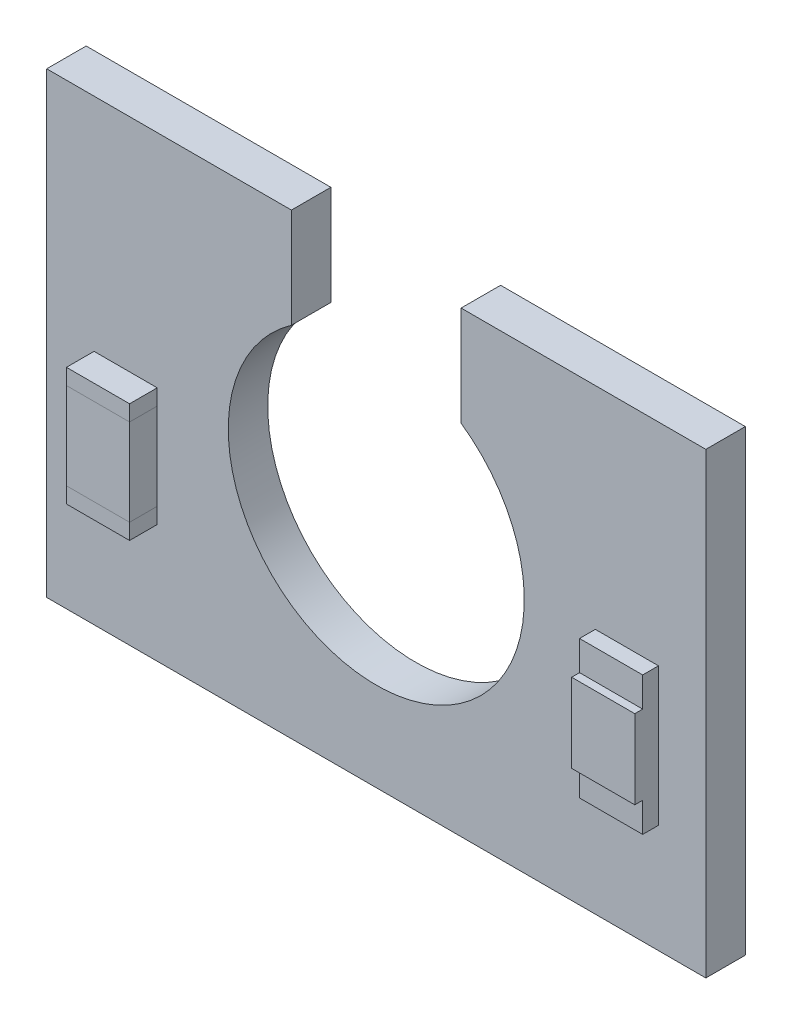
SolidWorks part; units mm, degrees
material "A-Glass Fiber"
ref_plane "Front Plane" through (0, 0, 0) normal (0, 0, 1) x (1, 0, 0)
ref_plane "Top Plane" through (0, 0, 0) normal (0, 1, 0) x (1, 0, 0)
ref_plane "Right Plane" through (0, 0, 0) normal (1, 0, 0) x (0, 0, -1)
sketch "BaseS" plane through (0, 0, 0) normal (0, 0, 1) x (1, 0, 0)
  line L1 (-8.35, 5.8) -> (8.35, 5.8)
  line L2 (-8.35, 5.8) -> (-8.35, -5.8)
  line L3 (-8.35, -5.8) -> (8.35, -5.8)
  line L4 (8.35, 5.8) -> (8.35, -5.8)
  line L5 (-8.35, 5.8) -> (8.35, -5.8) construction
  line L6 (-8.35, -5.8) -> (8.35, 5.8) construction
  point P0 (0, 0)
  dimension "D1" = 11.6
  dimension "D2" = 16.7
extrude "BASE" add sketch "BaseS" against normal blind 1
sketch "FastenerAccessS" plane through (0, 0, 0) normal (0, 0, 1) x (1, 0, 0)
  line L0 (0, -5.8) -> (0, 0.2) construction
  line L1 (-8.35, -5.8) -> (8.35, -5.8) construction
  line L2 (8.35, 5.8) -> (-8.35, 5.8) construction
  line L3 (-2.15, 5.8) -> (2.15, 5.8)
  line L4 (-2.15, 5.8) -> (-2.15, 3.2725)
  line L6 (2.15, 5.8) -> (2.15, 3.2725)
  arc A0 (-2.15, 3.2725) -> (2.15, 3.2725) centre (0, 0.2) ccw
  point P11 (0, 5.8)
  dimension "D1" = 7.5
  dimension "D2" = 6
  dimension "D3" = 4.3
extrude "FASTENER ACCESS" cut sketch "FastenerAccessS" against normal through all
sketch "SMDCapacitorBodyS" plane through (0, 0, 0) normal (0, 0, 1) x (1, 0, 0)
  line L0 (-8.35, -5.8) -> (8.35, -5.8) construction
  line L1 (-7.15, -0.2) -> (-5.55, -0.2)
  line L2 (-7.15, -0.2) -> (-7.15, -2.4)
  line L3 (-7.15, -2.4) -> (-5.55, -2.4)
  line L4 (-5.55, -0.2) -> (-5.55, -2.4)
  line L5 (-7.15, -0.2) -> (-5.55, -2.4) construction
  line L6 (-7.15, -2.4) -> (-5.55, -0.2) construction
  line L7 (-8.35, 5.8) -> (-8.35, -5.8) construction
  point P0 (-6.35, -1.3)
  dimension "D1" = 4.5
  dimension "D2" = 1.6
  dimension "D3" = 2.2
  dimension "D4" = 2
extrude "SMD CAPACITOR BODY" add sketch "SMDCapacitorBodyS" along normal blind 0.7 separate body
sketch "SMDCapacitorSolderBody1S" plane through (0, -2.4, 0) normal (0, -1, 0) x (1, 0, 0)
  line L4 (-7.15, 0) -> (-5.55, 0)
  line L5 (-5.55, 0) -> (-5.55, 0.7)
  line L6 (-5.55, 0.7) -> (-7.15, 0.7)
  line L7 (-7.15, 0.7) -> (-7.15, 0)
  line L8 (-7.15, 0) -> (-5.55, 0)
  line L9 (-5.55, 0) -> (-5.55, 0.7)
  line L10 (-5.55, 0.7) -> (-7.15, 0.7)
  line L11 (-7.15, 0.7) -> (-7.15, 0)
  dimension "D1" = 0
extrude "SMD CAPACITOR SOLDER BODY 1" add sketch "SMDCapacitorSolderBody1S" along normal blind 0.4 separate body
sketch "SMDCapacitorSolderBody2S" plane through (0, -0.2, 0) normal (0, 1, 0) x (1, 0, 0)
  line L4 (-5.55, 0) -> (-7.15, 0)
  line L5 (-7.15, 0) -> (-7.15, -0.7)
  line L6 (-7.15, -0.7) -> (-5.55, -0.7)
  line L7 (-5.55, -0.7) -> (-5.55, 0)
  line L8 (-5.55, 0) -> (-7.15, 0)
  line L9 (-7.15, 0) -> (-7.15, -0.7)
  line L10 (-7.15, -0.7) -> (-5.55, -0.7)
  line L11 (-5.55, -0.7) -> (-5.55, 0)
  dimension "D1" = 0
extrude "SMD CAPACITOR SOLDER BODY 2" add sketch "SMDCapacitorSolderBody2S" along normal blind 0.4 separate body
sketch "LEDS" plane through (0, 0, 0) normal (0, 0, 1) x (1, 0, 0)
  line L0 (-6.35, -1.3) -> (6.35, -1.3) construction
  line L1 (5.55, 0.45) -> (7.15, 0.45)
  line L2 (5.55, 0.45) -> (5.55, -3.05)
  line L3 (5.55, -3.05) -> (7.15, -3.05)
  line L4 (7.15, 0.45) -> (7.15, -3.05)
  line L5 (5.55, 0.45) -> (7.15, -3.05) construction
  line L6 (5.55, -3.05) -> (7.15, 0.45) construction
  line L7 (0, 0) -> (0, -1.3) construction
  point P0 (6.35, -1.3)
  dimension "D1" = 1.6
  dimension "D2" = 3.5
extrude "LED" add sketch "LEDS" along normal blind 0.4 separate body
sketch "LEDTS" plane through (0, 0, 0.4) normal (0, 0, 1) x (1, 0, 0)
  line L0 (7.15, -3.05) -> (7.15, 0.45) construction
  line L1 (5.55, -0.3) -> (7.15, -0.3)
  line L2 (5.55, -0.3) -> (5.55, -2.3)
  line L3 (5.55, -2.3) -> (7.15, -2.3)
  line L4 (7.15, -0.3) -> (7.15, -2.3)
  line L5 (5.55, -0.3) -> (7.15, -2.3) construction
  line L6 (5.55, -2.3) -> (7.15, -0.3) construction
  point P0 (6.35, -1.3)
  dimension "D1" = 2
extrude "LED TOP" add sketch "LEDTS" along normal blind 0.2
